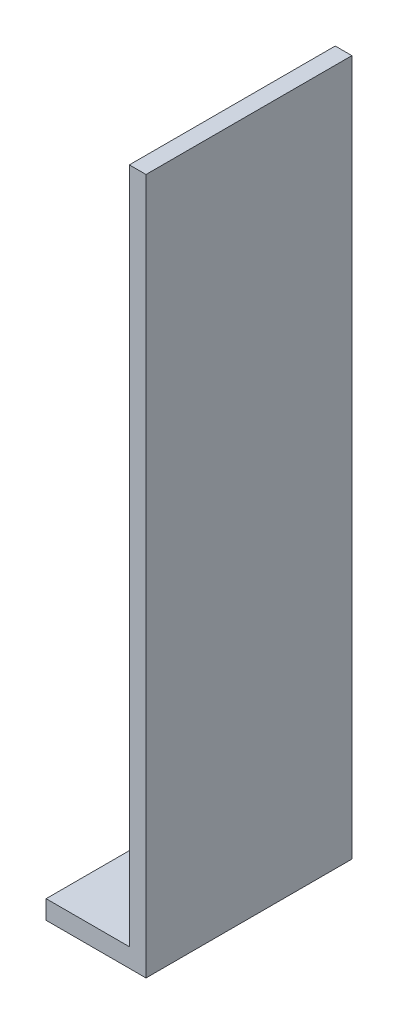
SolidWorks part; units mm, degrees
ref_plane "Front Plane" through (0, 0, 0) normal (0, 0, 1) x (1, 0, 0)
ref_plane "Top Plane" through (0, 0, 0) normal (0, 1, 0) x (1, 0, 0)
ref_plane "Right Plane" through (0, 0, 0) normal (1, 0, 0) x (0, 0, -1)
sketch "Sketch1" plane through (0, 0, 0) normal (0, 0, 1) x (1, 0, 0)
  line L0 (0, -65.1756) -> (24.2604, -65.1756)
  line L1 (24.2604, -65.1756) -> (24.2604, 103.8244)
  line L2 (24.2604, 103.8244) -> (20.2142, 103.8244)
  line L3 (20.2142, 103.8244) -> (20.2142, -60.62)
  line L4 (20.2142, -60.62) -> (0, -60.62)
  line L5 (0, -60.62) -> (0, -65.1756)
  line L6 (-39.263, -65.1756) -> (60.737, -65.1756) construction
  dimension "D1" = 169
extrude "Boss-Extrude1" add sketch "Sketch1" along normal blind 68
sketch "Sketch2" plane through (0, 0, 0) normal (0, 0, -1) x (-1, 0, 0)
  line L6 (0, -65.1756) -> (0, -60.62)
  line L7 (0, -60.62) -> (-20.2142, -60.62)
  line L8 (-20.2142, -60.62) -> (-20.2142, 103.8244)
  line L9 (-20.2142, 103.8244) -> (-24.2604, 103.8244)
  line L10 (-24.2604, 103.8244) -> (-24.2604, -65.1756)
  line L11 (-24.2604, -65.1756) -> (0, -65.1756)
  line L12 (0, -65.1756) -> (0, -60.62)
  line L13 (0, -60.62) -> (-20.2142, -60.62)
  line L14 (-20.2142, -60.62) -> (-20.2142, 103.8244)
  line L15 (-20.2142, 103.8244) -> (-24.2604, 103.8244)
  line L16 (-24.2604, 103.8244) -> (-24.2604, -65.1756)
  line L17 (-24.2604, -65.1756) -> (0, -65.1756)
  dimension "D1" = 0
extrude "Cut-Extrude1" cut sketch "Sketch2" against normal up to surface (18 mm away)
